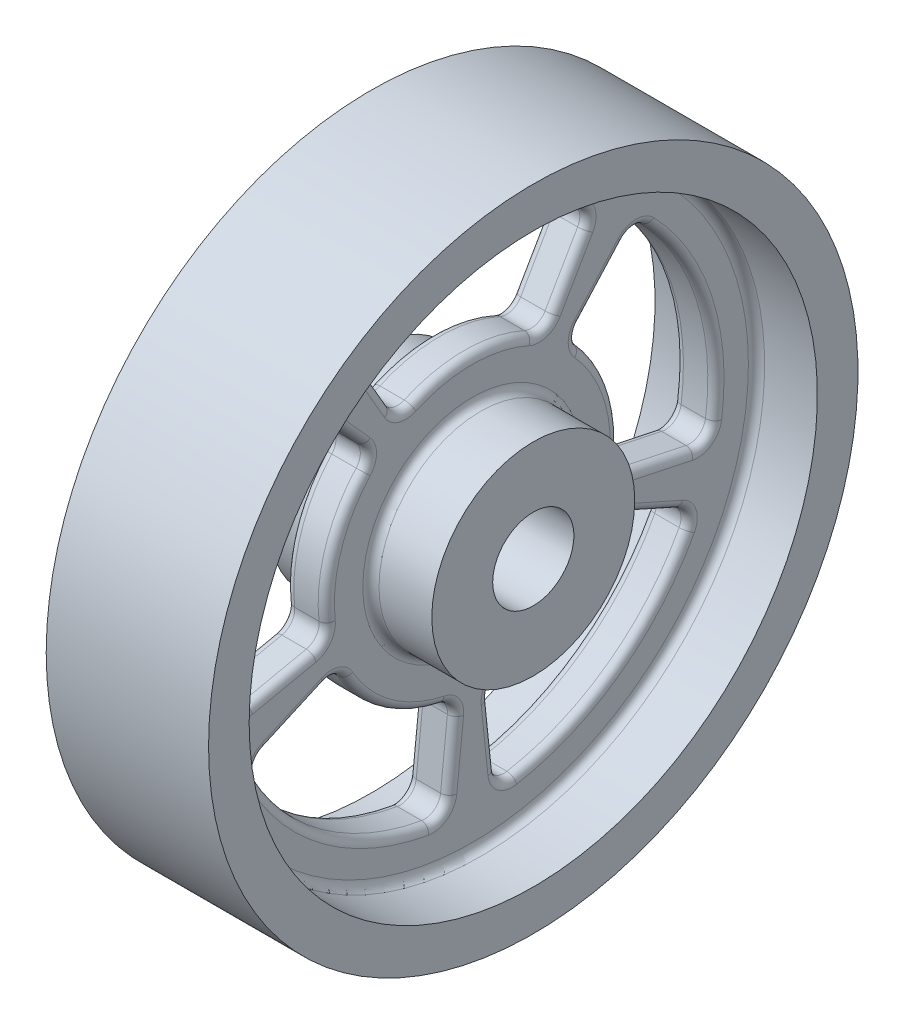
SolidWorks part; units mm, degrees
ref_plane "Front Plane" through (0, 0, 0) normal (0, 0, 1) x (1, 0, 0)
ref_plane "Top Plane" through (0, 0, 0) normal (0, 1, 0) x (1, 0, 0)
ref_plane "Right Plane" through (0, 0, 0) normal (1, 0, 0) x (0, 0, -1)
sketch "Sketch1" plane through (0, 0, 0) normal (0, 0, 1) x (1, 0, 0)
  line L0 (2.5, 35) -> (10, 35)
  line L1 (-10, 35) -> (-2.5, 35)
  line L2 (-10, 35) -> (-10, 40)
  line L3 (-10, 40) -> (10, 40)
  line L4 (10, 35) -> (10, 40)
  line L6 (-2.5, 35) -> (-2.5, 12.5)
  line L8 (2.5, 35) -> (2.5, 12.5)
  line L9 (-10, 12.5) -> (-2.5, 12.5)
  line L10 (-10, 12.5) -> (-10, 5)
  line L11 (-10, 5) -> (10, 5)
  line L12 (10, 12.5) -> (10, 5)
  line L13 (2.5, 12.5) -> (10, 12.5)
  line L14 (0, 0) -> (0, 47.3718) construction
  line L15 (0, 0) -> (20.4343, 0) construction
  dimension "D1" = 20
  dimension "D2" = 5
  dimension "D3" = 5
  dimension "D4" = 80
  dimension "D5" = 10
  dimension "D6" = 25
revolve "Revolve1" add sketch "Sketch1" angle 360 about L15
sketch "Sketch2" plane through (2.5, 0, 0) normal (1, 0, 0) x (0, 0, -1)
  line L0 (0, 0) -> (0, 50.8908) construction
  line L1 (-15, 25.9808) -> (-9, 15.5885)
  line L2 (15, 25.9808) -> (9, 15.5885)
  arc A0 (15, 25.9808) -> (-15, 25.9808) centre (0, 0) ccw
  arc A1 (9, 15.5885) -> (-9, 15.5885) centre (0, 0) ccw
  dimension "D1" = 30
  dimension "D2" = 18
  dimension "D3" = 60
extrude "Cut-Extrude1" cut sketch "Sketch2" against normal blind 10
fillet "Fillet2" radius 2 1 edges at (0, 25.9808, -15)
fillet "Fillet3" radius 2 2 edges at (0, 15.5885, 9) (0, 15.5885, -9)
fillet "Fillet4" radius 2 1 edges at (0, 25.9808, 15)
pattern_circular "CirPattern1" count 5 over 360 about axis through (0, 0, 0) along (1, 0, 0) of "Fillet3", "Fillet4", "Cut-Extrude1", "Fillet2"
fillet "Fillet5" radius 1 84 edges at (2.5, 0, 12.5) (2.5, 0, 35) (2.5, 16.3302, 8.8315) (2.5, 18, 0) (2.5, 16.3302, -8.8315) (2.5, 20.7102, -11.9571) (2.5, 25.7731, -14.1443) (2.5, 30, 0) (2.5, 25.7731, 14.1443) (2.5, 20.7102, 11.9571) (2.5, 13.4456, -12.8018) (2.5, 5.5623, -17.119) (2.5, -3.353, -18.26) (2.5, -4.972, -23.3915) (2.5, -5.4877, -28.8825) (2.5, 9.2705, -28.5317) (2.5, 21.4164, -20.1409) (2.5, 17.7717, -16.0017) (2.5, -8.0203, -16.7435) (2.5, -14.5623, -10.5801) (2.5, -18.4024, -2.4538) (2.5, -23.7831, -2.4997) (2.5, -29.1647, -3.7061) (2.5, -24.2705, -17.6336) (2.5, -12.5371, -26.592) (2.5, -9.7267, -21.8466) (2.5, -18.4024, 2.4538) (2.5, -14.5623, 10.5801) (2.5, -8.0203, 16.7435) (2.5, -9.7267, 21.8466) (2.5, -12.5371, 26.592) (2.5, -24.2705, 17.6336) (2.5, -29.1647, 3.7061) (2.5, -23.7831, 2.4997) (2.5, -3.353, 18.26) (2.5, 5.5623, 17.119) (2.5, 13.4456, 12.8018) (2.5, 17.7717, 16.0017) (2.5, 21.4164, 20.1409) (2.5, 9.2705, 28.5317) (2.5, -5.4877, 28.8825) (2.5, -4.972, 23.3915) (-2.5, 0, 35) (-2.5, 0, 12.5) (-2.5, 16.3302, 8.8315) (-2.5, 20.7102, 11.9571) (-2.5, 25.7731, 14.1443) (-2.5, 30, 0) (-2.5, 25.7731, -14.1443) (-2.5, 20.7102, -11.9571) (-2.5, 16.3302, -8.8315) (-2.5, 18, 0) (-2.5, 13.4456, -12.8018) (-2.5, 17.7717, -16.0017) (-2.5, 21.4164, -20.1409) (-2.5, 9.2705, -28.5317) (-2.5, -5.4877, -28.8825) (-2.5, -4.972, -23.3915) (-2.5, -3.353, -18.26) (-2.5, 5.5623, -17.119) (-2.5, -8.0203, -16.7435) (-2.5, -9.7267, -21.8466) (-2.5, -12.5371, -26.592) (-2.5, -24.2705, -17.6336) (-2.5, -29.1647, -3.7061) (-2.5, -23.7831, -2.4997) (-2.5, -18.4024, -2.4538) (-2.5, -14.5623, -10.5801) (-2.5, -18.4024, 2.4538) (-2.5, -23.7831, 2.4997) (-2.5, -29.1647, 3.7061) (-2.5, -24.2705, 17.6336) (-2.5, -12.5371, 26.592) (-2.5, -9.7267, 21.8466) (-2.5, -8.0203, 16.7435) (-2.5, -14.5623, 10.5801) (-2.5, -3.353, 18.26) (-2.5, -4.972, 23.3915) (-2.5, -5.4877, 28.8825) (-2.5, 9.2705, 28.5317) (-2.5, 21.4164, 20.1409) (-2.5, 17.7717, 16.0017) (-2.5, 13.4456, 12.8018) (-2.5, 5.5623, 17.119)
